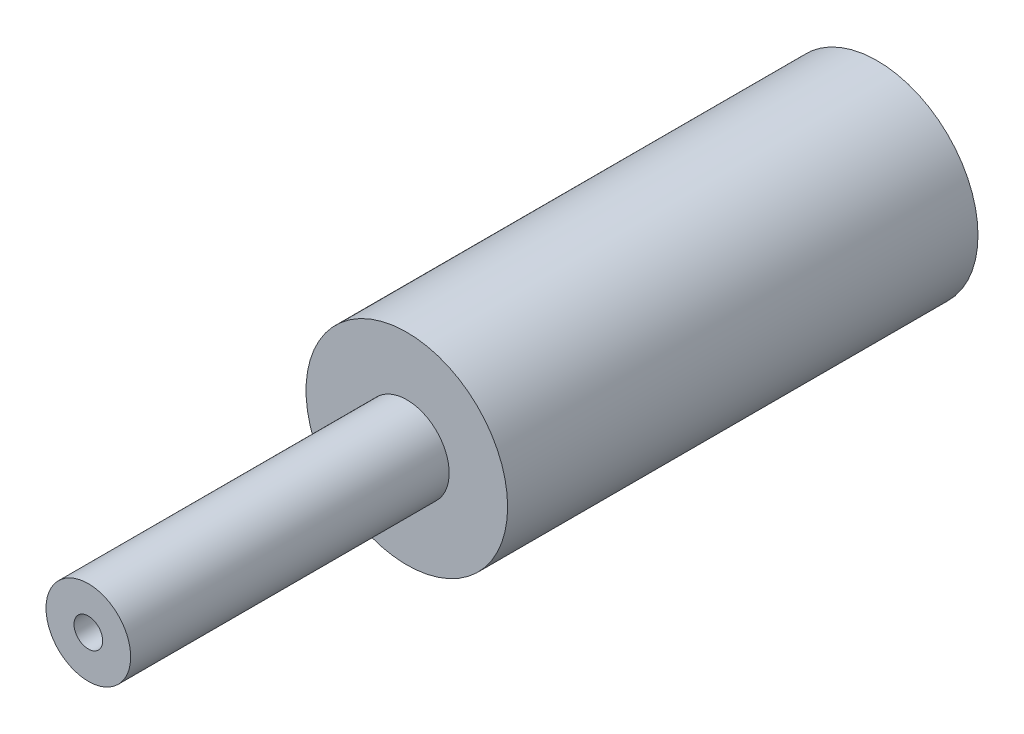
SolidWorks part; units mm, degrees
material "Cast Alloy Steel"
ref_plane "Front Plane" through (0, 0, 0) normal (0, 0, 1) x (1, 0, 0)
ref_plane "Top Plane" through (0, 0, 0) normal (0, 1, 0) x (1, 0, 0)
ref_plane "Right Plane" through (0, 0, 0) normal (1, 0, 0) x (0, 0, -1)
sketch "Sketch1" plane through (0, 0, 0) normal (0, 0, 1) x (1, 0, 0)
  circle A0 centre (0, 0) radius 9.525
  dimension "D1" = 19.05
extrude "Boss-Extrude1" add sketch "Sketch1" along normal blind 44.45
sketch "Sketch2" plane through (0, 0, 44.45) normal (0, 0, 1) x (1, 0, 0)
  circle A0 centre (0, 0) radius 4
  dimension "D1" = 8
extrude "Boss-Extrude2" add sketch "Sketch2" along normal blind 30.099
sketch "Sketch3" plane through (0, 0, 74.549) normal (0, 0, 1) x (1, 0, 0)
  circle A0 centre (0, 0) radius 1.3525
  dimension "D1" = 2.7051
extrude "Cut-Extrude1" cut sketch "Sketch3" against normal blind 17.78
